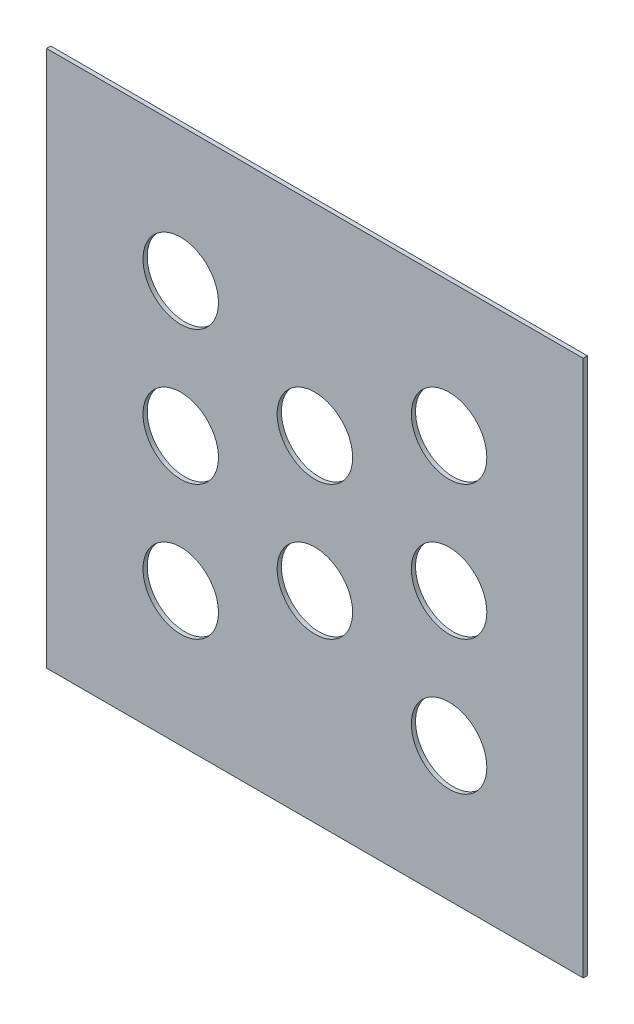
SolidWorks part; units mm, degrees
ref_plane "Front Plane" through (0, 0, 0) normal (0, 0, 1) x (1, 0, 0)
ref_plane "Top Plane" through (0, 0, 0) normal (0, 1, 0) x (1, 0, 0)
ref_plane "Right Plane" through (0, 0, 0) normal (1, 0, 0) x (0, 0, -1)
sketch "Sketch1" plane through (0, 0, 0) normal (0, 0, 1) x (1, 0, 0)
  line L1 (0, 0) -> (203.2, 0)
  line L2 (0, 0) -> (0, -203.2)
  line L3 (0, -203.2) -> (203.2, -203.2)
  line L4 (203.2, 0) -> (203.2, -203.2)
  circle A0 centre (152.4, -101.6) radius 14.2875
  circle A1 centre (152.4, -50.8) radius 14.2875
  circle A2 centre (101.6, -76.2) radius 14.2875
  circle A3 centre (152.4, -152.4) radius 14.2875
  circle A4 centre (50.8, -50.8) radius 14.2875
  circle A5 centre (50.8, -101.6) radius 14.2875
  circle A6 centre (50.8, -152.4) radius 14.2875
  circle A7 centre (101.6, -127) radius 14.2875
  dimension "D6" = 28.575
  dimension "D7" = 28.575
  dimension "D8" = 2
  dimension "D1" = 203.2
  dimension "D2" = 203.2
  dimension "D3" = 50.8
  dimension "D4" = 3
  dimension "D5" = 50.8
  dimension "D9" = 50.8
  dimension "D10" = 25.4
extrude "Boss-Extrude1" add sketch "Sketch1" along normal blind 1.5875
